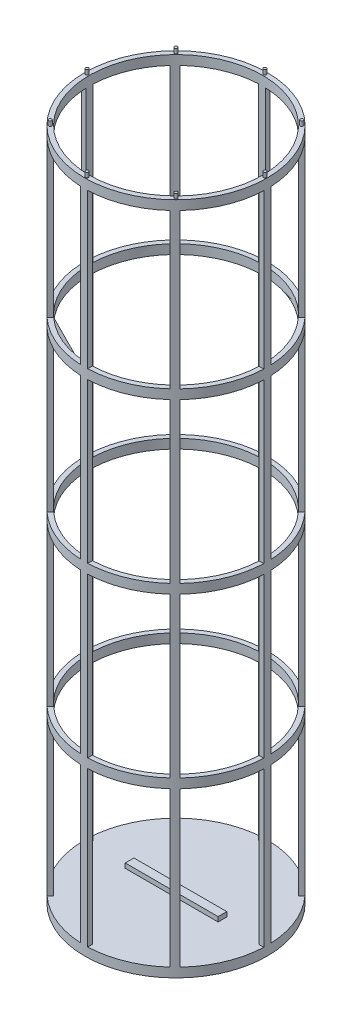
SolidWorks part; units mm, degrees
other "Markup1"
sketch "Sketch8" plane through (-49.53, -182.88, -49.53) normal (-0.9639, -0.2619, -0.0481) x (-0.0755, 0.0957, 0.9925)
ref_plane "Front Plane" through (0, 0, 0) normal (0, 0, 1) x (1, 0, 0)
ref_plane "Top Plane" through (0, 0, 0) normal (0, 1, 0) x (1, 0, 0)
ref_plane "Right Plane" through (0, 0, 0) normal (1, 0, 0) x (0, 0, -1)
sketch "Sketch1" plane through (0, 0, 0) normal (0, 1, 0) x (1, 0, 0)
  circle A0 centre (0, 0) radius 49.53
  circle A1 centre (0, 0) radius 46.99
  dimension "D1" = 99.06
  dimension "D2" = 93.98
extrude "Boss-Extrude1" add sketch "Sketch1" along normal mid plane 365.76
sketch "Sketch2" plane through (0, 0, 0) normal (0, 1, 0) x (1, 0, 0)
  line L0 (0, -49.53) -> (0, 49.53) construction
  line L1 (49.53, 0) -> (-49.53, 0) construction
  line L2 (36.1361, -33.8733) -> (-33.8733, 36.1361)
  line L3 (49.4953, -1.8543) -> (-49.4953, -1.8543)
  line L5 (49.4914, 1.9557) -> (-49.4914, 1.9557)
  line L7 (49.5079, -1.4801) -> (-49.5079, 1.4801) construction
  line L8 (49.5079, 1.4801) -> (-49.5079, -1.4801) construction
  line L10 (-2.2251, -49.48) -> (-2.2251, 49.48)
  line L12 (1.5849, -49.5046) -> (1.5849, 49.5046)
  line L13 (-2.0946, -49.4857) -> (2.0946, 49.4857) construction
  line L14 (-2.0946, 49.4857) -> (2.0946, -49.4857) construction
  line L17 (33.4254, -36.5508) -> (-36.5508, 33.4254)
  line L18 (36.2203, -33.7833) -> (-36.2203, 33.7833) construction
  line L19 (-33.7833, 36.2203) -> (33.7833, -36.2203) construction
  line L20 (-36.2459, -33.7558) -> (33.7558, 36.2459)
  line L23 (-33.544, -36.4421) -> (36.4421, 33.544)
  line L24 (-35.9086, -34.1144) -> (35.9086, 34.1144) construction
  line L25 (34.1144, 35.9086) -> (-34.1144, -35.9086) construction
  line L26 (42.4888, -20.0689) -> (-44.235, 15.8533)
  line L29 (43.9751, -16.5606) -> (-42.8052, 19.385)
  line L30 (42.7791, -19.4425) -> (-42.7791, 19.4425) construction
  line L31 (-43.9973, 16.5014) -> (43.9973, -16.5014) construction
  line L32 (19.1177, -42.9252) -> (-16.8344, 43.871)
  line L35 (15.577, -44.333) -> (-20.3336, 42.3628)
  line L36 (19.8255, -42.6029) -> (-19.8255, 42.6029) construction
  line L37 (-16.1061, 44.1436) -> (16.1061, -44.1436) construction
  line L38 (-16.6796, -43.9301) -> (19.2689, 42.8575)
  line L41 (-20.184, -42.4343) -> (15.7333, 44.2778)
  line L42 (-16.127, -44.1359) -> (16.127, 44.1359) construction
  line L43 (19.8053, 42.6123) -> (-19.8053, -42.6123) construction
  line L44 (-44.26, -15.7832) -> (42.457, 20.1362)
  line L47 (-42.8358, -19.3171) -> (43.9488, 16.6302)
  line L48 (-44.0599, -16.3335) -> (44.0599, 16.3335) construction
  line L49 (42.7046, 19.6055) -> (-42.7046, -19.6055) construction
  circle A0 centre (0, 0) radius 49.53
  circle A1 centre (0, 0) radius 46.99
  point P7 (0, 0)
  point P10 (0, 0)
  dimension "D1" = 45
  dimension "D2" = 45
  dimension "D3" = 22.5
  dimension "D4" = 22.5
  dimension "D5" = 22.5
  dimension "D6" = 22.5
  dimension "D7" = 3.81
  dimension "D8" = 3.81
  dimension "D9" = 3.81
  dimension "D10" = 3.81
  dimension "D11" = 3.81
  dimension "D12" = 3.81
  dimension "D13" = 3.81
  dimension "D14" = 3.81
extrude "Cut-Extrude1" cut sketch "Sketch2" against normal mid plane 355.6 contours A1 L10 A0 L2 | A1 L17 A0 L5 | A1 L3 A0 L20 | A1 L23 A0 L10 | A1 L12 A0 L17 | A1 L2 A0 L3 | A1 L5 A0 L23 | A1 L20 A0 L12 L35
ref_plane "Plane1" through (0, 91.44, 0) normal (0, 1, 0) x (1, 0, 0)
sketch "Sketch3" plane through (0, 91.44, 0) normal (0, 1, 0) x (1, 0, 0)
  circle A0 centre (0, 0) radius 46.99
  circle A1 centre (0, 0) radius 49.53
extrude "Boss-Extrude2" add sketch "Sketch3" along normal mid plane 5.08
mirror "Mirror1" about plane through (0, 0, 0) normal (0, 1, 0) of "Boss-Extrude2"
sketch "Sketch4" plane through (0, 0, 0) normal (0, 1, 0) x (1, 0, 0)
  circle A0 centre (0, 0) radius 46.99
  circle A1 centre (0, 0) radius 49.53
extrude "Boss-Extrude3" add sketch "Sketch4" along normal mid plane 5.08
sketch "Sketch5" plane through (0, -182.88, 0) normal (0, -1, 0) x (1, 0, 0)
  circle A0 centre (0, 0) radius 49.53
extrude "Boss-Extrude4" add sketch "Sketch5" against normal blind 5.08
sketch "Sketch6" plane through (0, -177.8, 0) normal (0, 1, 0) x (1, 0, 0)
  line L0 (0, -49.53) -> (0, 49.53) construction
  line L1 (49.53, 0) -> (-49.53, 0) construction
  line L3 (25.2095, -2.3495) -> (-25.2095, -2.3495)
  line L4 (25.2095, -2.3495) -> (25.2095, 2.3495)
  line L5 (25.2095, 2.3495) -> (-25.2095, 2.3495)
  line L6 (-25.2095, -2.3495) -> (-25.2095, 2.3495)
  line L7 (25.2095, -2.3495) -> (-25.2095, 2.3495) construction
  line L8 (25.2095, 2.3495) -> (-25.2095, -2.3495) construction
  circle A0 centre (0, 0) radius 49.53 construction
  point P0 (0, 0)
  point P7 (0, 0)
  point P11 (0, 0)
  dimension "D1" = 50.419
  dimension "D2" = 4.699
extrude "Boss-Extrude5" add sketch "Sketch6" along normal blind 2.54
sketch "Sketch7" plane through (0, 182.88, 0) normal (0, 1, 0) x (1, 0, 0)
  line L0 (0, 49.53) -> (0, -49.53) construction
  line L1 (49.53, 0) -> (46.99, 0) construction
  line L2 (0, 0) -> (-49.53, 0) construction
  circle A1 centre (0, 0) radius 49.53 construction
  circle A2 centre (0, 0) radius 46.99 construction
  circle A3 centre (48.26, 0) radius 0.8255
  point P8 (0, 0)
  point P11 (0, 0)
  dimension "D1" = 1.651
  dimension "D2" = 1.27
extrude "Boss-Extrude6" add sketch "Sketch7" along normal blind 2.54
pattern_circular "CirPattern2" count 8 over 360 about axis through (0, 0, 0) along (0, 1, 0) of "Boss-Extrude6"
